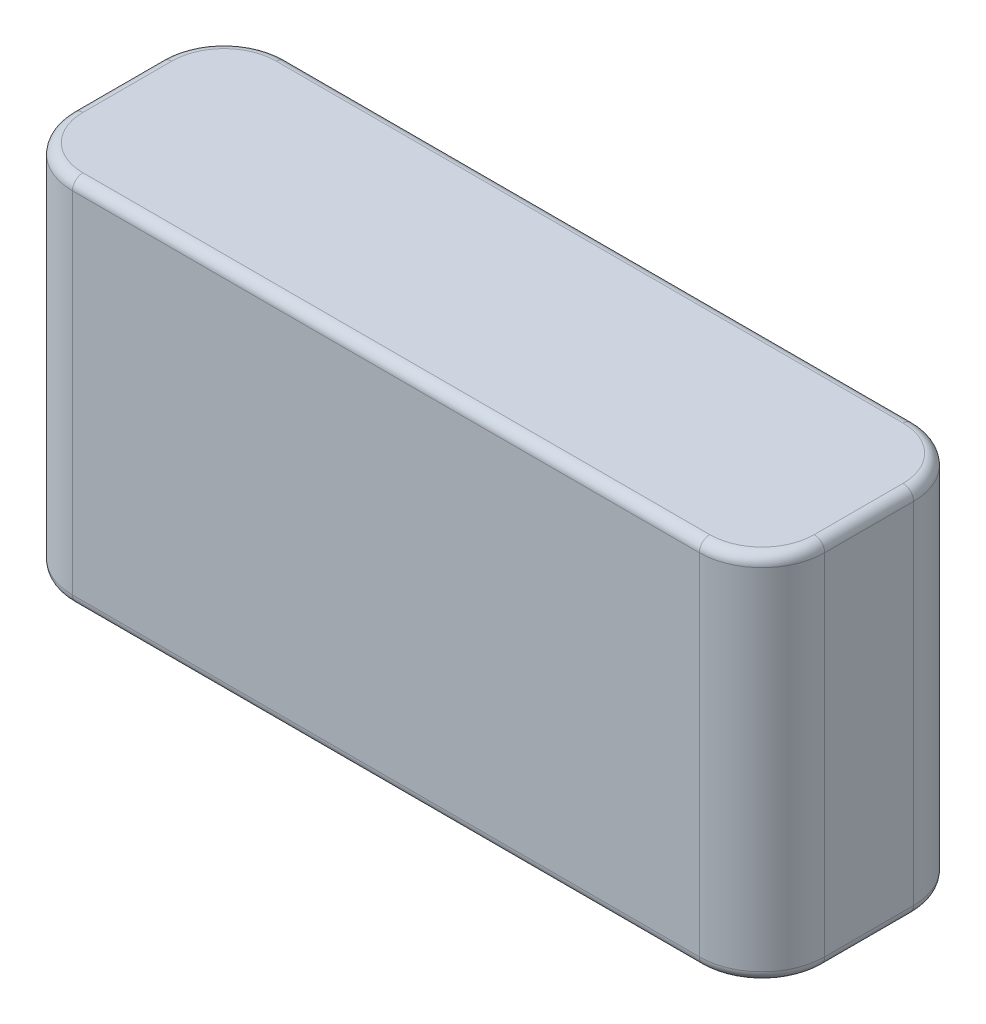
SolidWorks part; units mm, degrees
ref_plane "前视基准面" through (0, 0, 0) normal (0, 0, 1) x (1, 0, 0)
ref_plane "上视基准面" through (0, 0, 0) normal (0, 1, 0) x (1, 0, 0)
ref_plane "右视基准面" through (0, 0, 0) normal (1, 0, 0) x (0, 0, -1)
sketch "草图1" plane through (0, 0, 0) normal (0, 0, 1) x (1, 0, 0)
  line L1 (-36, -17.75) -> (36, -17.75)
  line L2 (-36, -17.75) -> (-36, 17.75)
  line L3 (-36, 17.75) -> (36, 17.75)
  line L4 (36, -17.75) -> (36, 17.75)
  line L5 (-36, -17.75) -> (36, 17.75) construction
  line L6 (-36, 17.75) -> (36, -17.75) construction
  point P0 (0, 0)
  dimension "D1" = 72
  dimension "D2" = 35.5
extrude "凸台-拉伸1" add sketch "草图1" along normal blind 20.5
fillet "圆角1" radius 6 4 edges at (-36, 0, 0) (-36, 0, 20.5) (36, 0, 0) (36, 0, 20.5)
fillet "圆角2" radius 1 16 edges at (34.2426, 17.75, 1.7574) (36, 17.75, 10.25) (34.2426, 17.75, 18.7426) (0, 17.75, 20.5) (-34.2426, 17.75, 18.7426) (-36, 17.75, 10.25) (-34.2426, 17.75, 1.7574) (0, 17.75, 0) (-34.2426, -17.75, 18.7426) (0, -17.75, 20.5) (34.2426, -17.75, 18.7426) (36, -17.75, 10.25) (34.2426, -17.75, 1.7574) (0, -17.75, 0) (-34.2426, -17.75, 1.7574) (-36, -17.75, 10.25)
